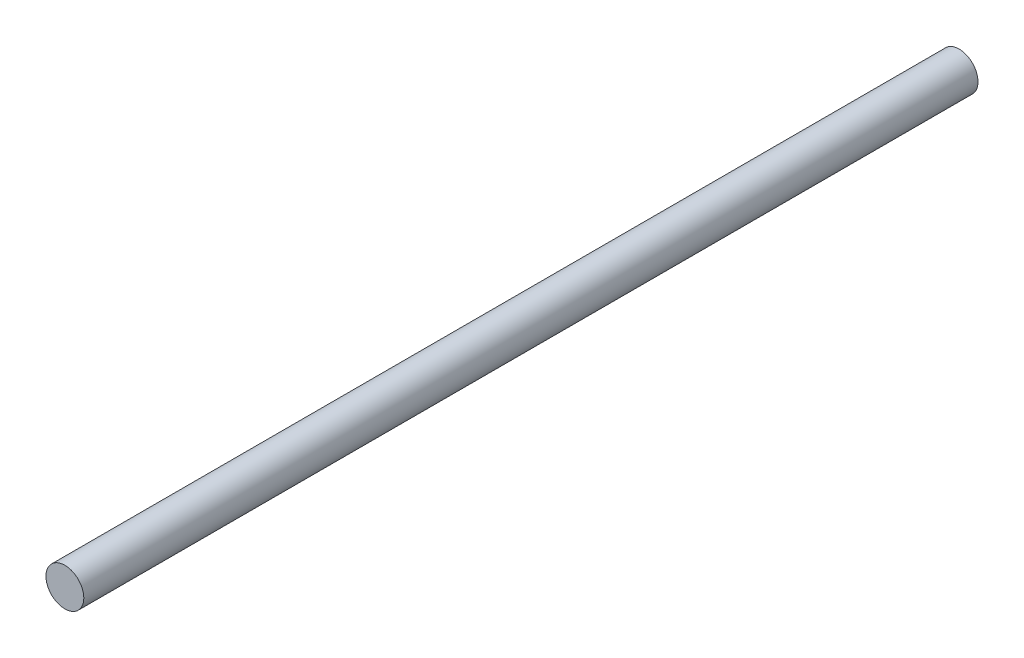
SolidWorks part; units mm, degrees
ref_plane "正面" through (0, 0, 0) normal (0, 0, 1) x (1, 0, 0)
ref_plane "平面" through (0, 0, 0) normal (0, 1, 0) x (1, 0, 0)
ref_plane "右側面" through (0, 0, 0) normal (1, 0, 0) x (0, 0, -1)
sketch "ｽｹｯﾁ1" plane through (0, 0, 0) normal (0, 0, 1) x (1, 0, 0)
  circle A0 centre (0, 0) radius 2.75
  dimension "D1" = 5.5
extrude "ﾎﾞｽ - 押し出し1" add sketch "ｽｹｯﾁ1" along normal blind 130
